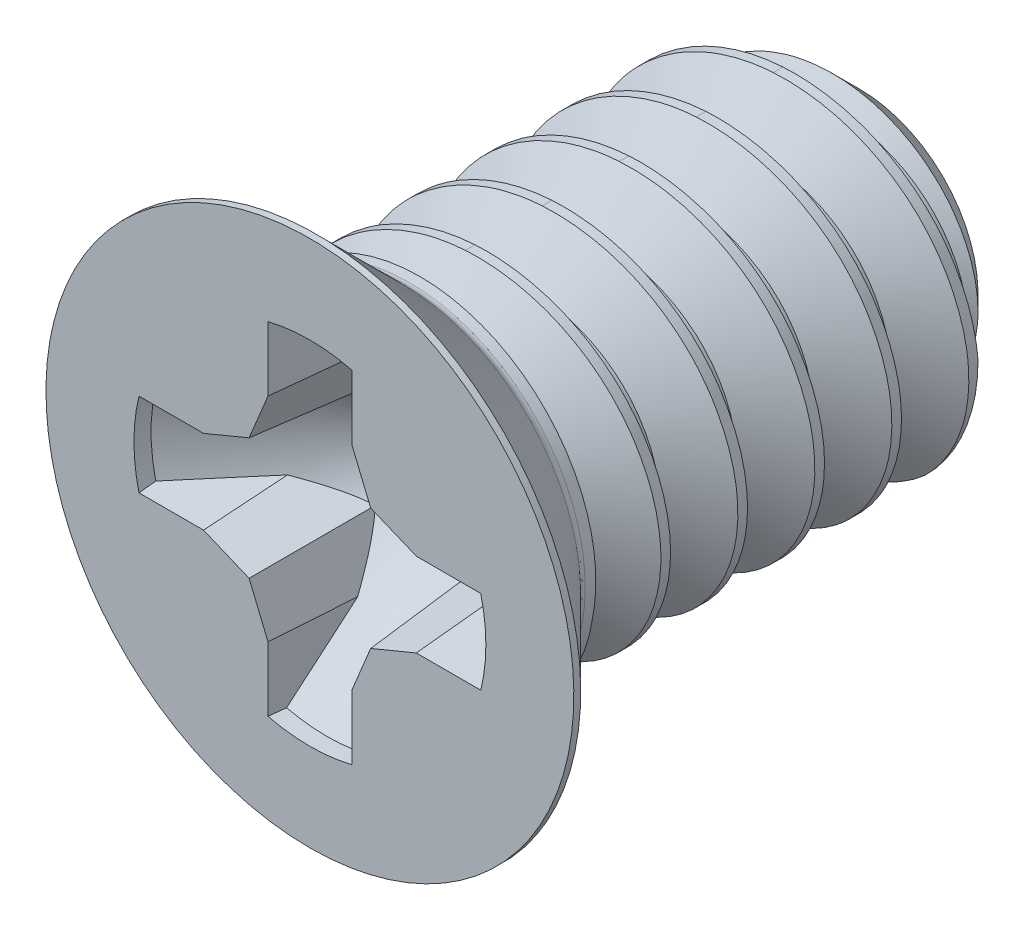
SolidWorks part; units mm, degrees
ref_plane "Front Plane" through (0, 0, 0) normal (0, 0, 1) x (1, 0, 0)
ref_plane "Top Plane" through (0, 0, 0) normal (0, 1, 0) x (1, 0, 0)
ref_plane "Right Plane" through (0, 0, 0) normal (1, 0, 0) x (0, 0, -1)
sketch "Sketch1" plane through (0, 0, 0) normal (1, 0, 0) x (0, 0, -1)
  line L0 (0, 0) -> (-0.5, 0) construction
  line L1 (-0.5, 1.2) -> (-0.5, -1.2) construction
  line L2 (-0.5, 1.2) -> (0, 0.7) construction
  line L3 (-0.5, -1.2) -> (0, -0.7) construction
  line L4 (0, 0.8) -> (0, -0.8) construction
  line L5 (0, 0) -> (2, 0) construction
  line L6 (0, 0.8) -> (0.35, 0.8) construction
  point P6 (1.475, -0.8)
  point P11 (0, 0)
  point P12 (0, 0.8)
  point P15 (0, 0)
  point P16 (-0.5, 0)
  dimension "Head Height" = 0.5
  dimension "Head Diameter" = 2.4
  dimension "Countersink Angle" = 90
  dimension "Screw Size Decimal Equivalent" = 1.6
  dimension "Length" = 2.5
  dimension "Pitch" = 0.35
  dimension "D1" = 0.525
sketch "Sketch2" plane through (0, 0, 0) normal (0, 0, 1) x (1, 0, 0)
  line L0 (0.1905, 0.8) -> (-0.1905, 0.8) construction
  circle A0 centre (0, 0) radius 0.8 construction
  point P3 (0, 0.8)
  point P4 (0, -0.8)
  point P7 (0, 0.8)
  dimension "Drive Diameter" = 1.6
  dimension "Drive Width" = 0.381
sketch "Sketch3" plane through (0, 0, 0) normal (1, 0, 0) x (0, 0, -1)
  line L0 (-0.5, 0) -> (-0.5, 1.2)
  line L1 (-0.4688, 1.2) -> (-0.0688, 0.8)
  line L3 (0, 0.8) -> (0.35, 0.8) construction
  line L4 (-0.5, 0) -> (-0.0688, 0)
  line L5 (0, 0) -> (-0.5, 0) construction
  line L6 (-0.0688, 0) -> (-0.0688, 0.8)
  line L7 (-0.5, 1.2) -> (0, 0.7) construction
  line L8 (-0.5, 1.2) -> (-0.4688, 1.2)
  dimension "D1" = 0.0312
revolve "Revolve1" add sketch "Sketch3" angle 360 about L4
sketch "Sketch5" plane through (0, 0, 0) normal (1, 0, 0) x (0, 0, -1)
  line L0 (2, 0) -> (-0.0688, 0)
  line L1 (0, 0) -> (2, 0) construction
  line L2 (-0.0688, 0) -> (-0.0688, 0.8)
  line L3 (-0.0688, 0.8) -> (1.7375, 0.8)
  line L4 (1.7375, 0.8) -> (2, 0.5375)
  line L5 (2, 0.5375) -> (2, 0)
  line L6 (1.7375, 0.8) -> (2, 0.8) construction
  line L7 (2, 0.8) -> (2, 0.5375) construction
  line L8 (0, 0.8) -> (0.35, 0.8) construction
  line L9 (-0.0688, -0.8) -> (-0.0688, 0.8) construction
  dimension "D1" = 0.2625
revolve "Revolve2" add sketch "Sketch5" angle 360 about L0
sketch "Sketch4" plane through (0, 0, 0.5) normal (0, 0, 1) x (1, 0, 0)
  line L0 (0, 0) -> (0, 0.8)
  line L1 (0, 0) -> (0.8, 0)
  line L2 (0, 0) -> (0.4837, 0.4837) construction
  line L3 (0.1905, 0.777) -> (0.1905, 0.4837)
  line L4 (0.1905, 0.4837) -> (0.1905, 0.1905) construction
  line L5 (0.4837, 0.1905) -> (0.1905, 0.1905) construction
  line L6 (0.777, 0.1905) -> (0.4837, 0.1905)
  line L7 (0.1905, 0.4837) -> (0.2764, 0.2764)
  line L8 (0.2764, 0.2764) -> (0.4837, 0.1905)
  line L9 (0, 0.8) -> (0, 1.2312) construction
  line L10 (0, 1.2) -> (0, -1.2) construction
  arc A1 (0, 0.8) -> (0.1905, 0.777) centre (0, 0) cw
  arc A2 (0.8, 0) -> (0.777, 0.1905) centre (0, 0) ccw
  arc A3 (0.4837, 0.1905) -> (0.1905, 0.4837) centre (0.4837, 0.4837) cw construction
  circle A4 centre (0, 0) radius 1.2312 construction
  point P8 (0.2764, 0.2764)
extrude "Cut-Extrude1" cut sketch "Sketch4" against normal offset from surface (0.8777 mm away) 0.25 contours L1 A2 L6 L8 L7 L3 A1 L0
pattern_circular "CirPattern1" count 4 over 360 about axis through (0, 0, 0) along (0, 0, 1) of "Cut-Extrude1"
draft "Draft2" type of draft neutral plane draft angle 5 faces to draft 16 face at (-0.667, 0.1905, 0.4261) face at (-0.406, 0.2227, 0.305) face at (-0.2442, 0.3541, 0.2727) face at (-0.1905, 0.667, 0.4261) face at (0.1905, 0.667, 0.4261) face at (0.2227, 0.406, 0.305) face at (0.3541, 0.2442, 0.2727) face at (0.667, 0.1905, 0.4261) face at (0.667, -0.1905, 0.4261) face at (0.406, -0.2227, 0.305) face at (0.2442, -0.3541, 0.2727) face at (0.1905, -0.667, 0.4261) face at (-0.1905, -0.667, 0.4261) face at (-0.2227, -0.406, 0.305) face at (-0.3541, -0.2442, 0.2727) face at (-0.667, -0.1905, 0.4261) neutral plane through (0, 0, 0.5) neutral plane normal (0, 0, 1) parameters "D1"=5
fillet "Fillet1" radius 0.05 1 edges at (0, 0.8, 0.0688)
ref_plane "Plane1" through (0, 0, 0) normal (0, 0, -1) x (-1, 0, 0)
split "Split1" trim tools "Plane1" bodies to split 107 105 resulting bodies 108 109
sketch "Sketch6" plane through (0, 0, -2) normal (0, 0, 1) x (1, 0, 0)
  circle A1 centre (0, 0) radius 0.8
  circle A2 centre (0, 0) radius 0.8
  dimension "D1" = 0
curve "Helix/Spiral1" pitch 0.35 height 2.5 turns 7.1429
sketch "Sketch7" plane through (0, 0, 0) normal (1, 0, 0) x (0, 0, -1)
  line L0 (1.9781, 0.8379) -> (2.3281, 0.8379) construction
  line L1 (1.9781, 0.8379) -> (2.1531, 0.5348) construction
  line L2 (2.1531, 0.5348) -> (2.3281, 0.8379) construction
  line L3 (2.1313, 0.5727) -> (2.175, 0.5727) construction
  line L4 (2, 0.8) -> (2.3063, 0.8) construction
  line L5 (2.1531, 0.8) -> (2.1531, 0.8379) construction
  line L6 (2.1531, 0.5727) -> (2.1531, 0.5348) construction
  line L7 (2.1531, 0.8189) -> (1.9891, 0.8189) construction
  line L10 (2.175, 0.5727) -> (2.1313, 0.5727)
  line L11 (1.9891, 0.8189) -> (2.1313, 0.5727)
  line L12 (1.9891, 0.8189) -> (2.3172, 0.8189)
  line L13 (2.3172, 0.8189) -> (2.175, 0.5727)
  line L14 (2.1531, 0.8) -> (2.1531, -0.8) construction
  line L15 (2.1531, -0.8) -> (1.8031, -0.8) construction
  line L16 (1.8031, -0.8) -> (1.4531, -0.8) construction
  line L17 (1.4531, -0.8) -> (1.1031, -0.8) construction
  line L18 (1.1031, -0.8) -> (0.7531, -0.8) construction
  line L19 (0.7531, -0.8) -> (0.4031, -0.8) construction
  point P16 (2.1531, 0)
  point P23 (1.1031, -0.8)
  point P24 (1.4531, -0.8)
  point P25 (0.7531, -0.8)
  point P26 (0.4031, -0.8)
  dimension "D1" = 0.35
  dimension "D2" = 0.0437
sweep "Cut-Sweep1" cut profiles "Sketch7" path "Helix/Spiral1"
combine bodies "Combine1" operation type add bodies to combine 109 110
equation "\"D1@Sketch5\"=\"Pitch@Sketch1\"*.75"
equation "\"D4@Helix/Spiral1\"=\"Pitch@Sketch1\""
equation "\"D3@Helix/Spiral1\"=\"Length@Sketch1\""
equation "\"D1@Sketch7\"=\"Pitch@Sketch1\""
equation "\"D2@Sketch7\"=\"Pitch@Sketch1\"/8"
equation "\"D1@Cut-Extrude1\"=\"Head Height@Sketch1\"*.5"
equation "\"D1@Sketch3\"=\"Head height@Sketch1\"*.0625"
equation "\"D1@Fillet1\"=\"Screw Size Decimal Equivalent@Sketch1\"*.03125"
equation "\"D1@Sketch1\"=\"Pitch@Sketch1\"*1.5"
